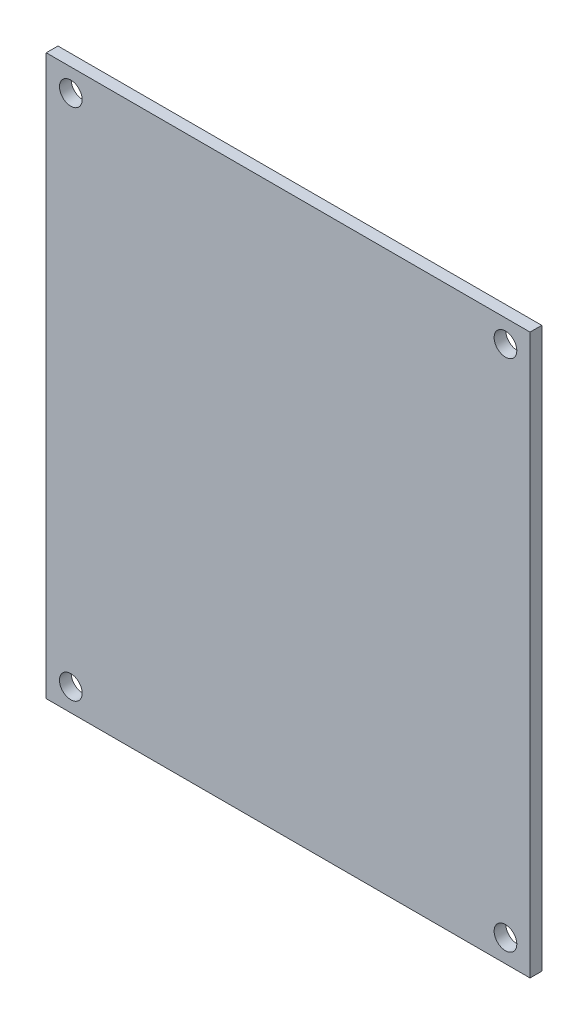
SolidWorks part; units mm, degrees
ref_plane "前视基准面" through (0, 0, 0) normal (0, 0, 1) x (1, 0, 0)
ref_plane "上视基准面" through (0, 0, 0) normal (0, 1, 0) x (1, 0, 0)
ref_plane "右视基准面" through (0, 0, 0) normal (1, 0, 0) x (0, 0, -1)
sketch "草图1" plane through (0, 0, 0) normal (0, 0, 1) x (1, 0, 0)
  line L1 (-32, -37) -> (32, -37)
  line L2 (-32, -37) -> (-32, 37)
  line L3 (-32, 37) -> (32, 37)
  line L4 (32, -37) -> (32, 37)
  line L5 (-32, -37) -> (32, 37) construction
  line L6 (-32, 37) -> (32, -37) construction
  point P0 (0, 0)
  dimension "D1" = 74
  dimension "D2" = 64
extrude "凸台-拉伸1" add sketch "草图1" along normal blind 1.55
sketch "草图2" plane through (0, 0, 1.55) normal (0, 0, 1) x (1, 0, 0)
  line L1 (-28.75, -34) -> (28.75, -34) construction
  line L2 (-28.75, -34) -> (-28.75, 34) construction
  line L3 (-28.75, 34) -> (28.75, 34) construction
  line L4 (28.75, -34) -> (28.75, 34) construction
  line L5 (-28.75, -34) -> (28.75, 34) construction
  line L6 (-28.75, 34) -> (28.75, -34) construction
  circle A0 centre (-28.75, 34) radius 1.5
  circle A1 centre (28.75, 34) radius 1.5
  circle A2 centre (28.75, -34) radius 1.5
  circle A3 centre (-28.75, -34) radius 1.5
  point P0 (0, 0)
  dimension "D3" = 3
  dimension "D4" = 3
  dimension "D5" = 3
  dimension "D6" = 3
  dimension "D1" = 68
  dimension "D2" = 57.5
extrude "切除-拉伸1" cut sketch "草图2" against normal blind 1.55
